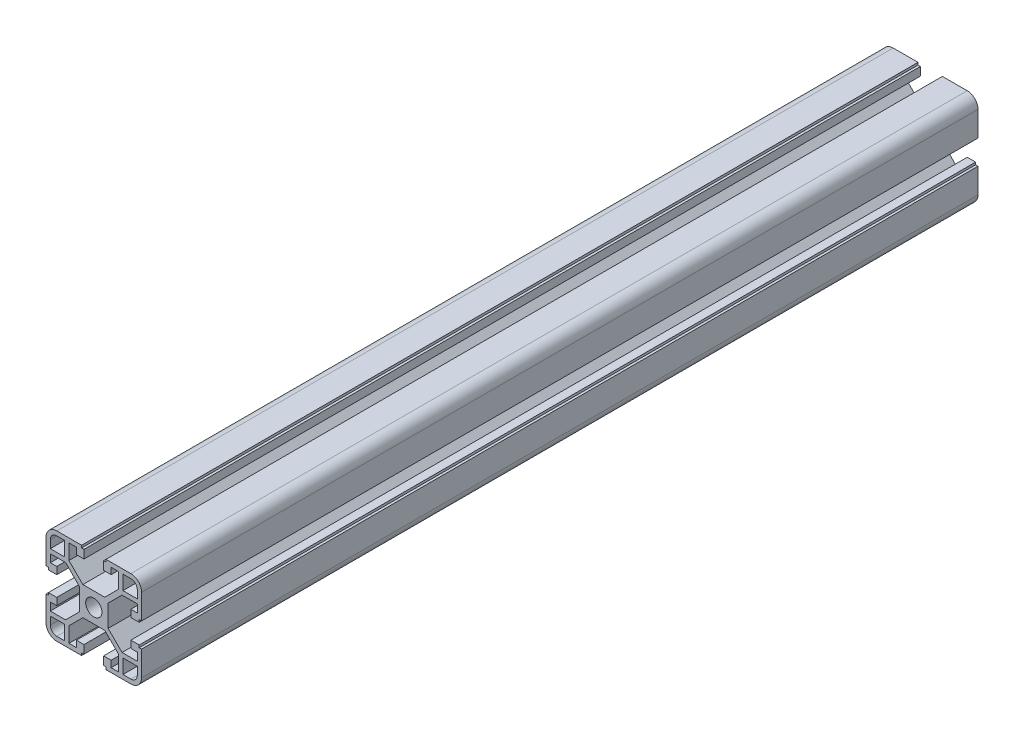
SolidWorks part; units mm, degrees
material "6063-T5"
ref_plane "Front Plane" through (0, 0, 0) normal (0, 0, 1) x (1, 0, 0)
ref_plane "Top Plane" through (0, 0, 0) normal (0, 1, 0) x (1, 0, 0)
ref_plane "Right Plane" through (0, 0, 0) normal (1, 0, 0) x (0, 0, -1)
sketch "Sketch3" plane through (0, 0, 0) normal (0, 0, 1) x (1, 0, 0)
  line L0 (17.9333, 92.7) -> (169.2667, 92.7) construction
  line L1 (-6, 6) -> (6, 6)
  line L2 (-6, 6) -> (-6, -6)
  line L3 (-6, -6) -> (6, -6)
  line L4 (6, 6) -> (6, -6)
  line L5 (0, 0) -> (20.1249, 20.1249) construction
  line L6 (4.5736, 4.5736) -> (11.4537, 11.4537) construction
  line L7 (5.2807, 3.8665) -> (12.0153, 10.6011)
  line L8 (3.8665, 5.2807) -> (10.7858, 12.2)
  line L13 (11.8142, 10.4) -> (18.2, 10.4)
  line L14 (6, 0) -> (23.1042, 0) construction
  line L15 (0, 6) -> (0, 13.9346) construction
  line L16 (4.5736, 4.5736) -> (11.8129, 11.8129) construction
  line L17 (5.2807, 3.8665) -> (12.52, 11.1058) construction
  line L18 (3.8665, 5.2807) -> (11.1058, 12.52) construction
  line L19 (10.4, 11.8142) -> (10.4, 18.2)
  line L20 (10.4, 18.2) -> (7.2581, 18.2)
  line L21 (-20, 20) -> (20, 20) construction
  line L22 (-20, 20) -> (-20, -20) construction
  line L23 (-20, -20) -> (20, -20) construction
  line L24 (20, 20) -> (20, -20) construction
  line L25 (7.2581, 18.2) -> (7.2581, 15.5)
  line L26 (7.2581, 15.5) -> (4.1, 15.5)
  line L27 (4.1, 15.5) -> (4.1, 19)
  line L28 (4.1, 19) -> (5.1, 19)
  line L29 (5.1, 19) -> (5.1, 20)
  line L30 (5.1, 20) -> (15.5, 20)
  line L31 (20, 15.5) -> (20, 5.1)
  line L32 (20, 5.1) -> (19, 5.1)
  line L33 (19, 5.1) -> (19, 4.1)
  line L34 (19, 4.1) -> (15.5, 4.1)
  line L35 (15.5, 4.1) -> (15.5, 7.1)
  line L36 (15.5, 7.1) -> (18.2, 7.1)
  line L37 (18.2, 7.1) -> (18.2, 10.4)
  line L42 (18.2, 12.2) -> (12.2, 12.2)
  line L43 (12.2, 18.2) -> (12.2, 18.2)
  line L44 (12.2, 18.2) -> (12.2, 18.2)
  line L45 (12.2, 18.2) -> (12.2, 18.2)
  line L46 (12.2, 18.2) -> (12.2, 18.2)
  line L47 (12.2, 18.2) -> (12.2, 18.2)
  line L48 (12.2, 18.2) -> (12.2, 18.2)
  line L49 (12.2, 18.2) -> (15.5, 18.2)
  line L50 (18.2, 15.5) -> (18.2, 12.2)
  line L51 (18.2, 12.2) -> (18.2, 12.2)
  line L52 (18.2, 12.2) -> (18.2, 12.2)
  line L53 (18.2, 12.2) -> (18.2, 12.2)
  line L54 (18.2, 12.2) -> (18.2, 12.2)
  line L55 (18.2, 12.2) -> (18.2, 12.2)
  line L56 (18.2, 12.2) -> (18.2, 12.2)
  line L57 (12.2, 12.2) -> (12.2, 18.2)
  line L58 (11.8142, 12.2) -> (18.2, 12.2) construction
  line L59 (12.2, 11.8142) -> (12.2, 18.2) construction
  line L60 (-18.2, 15.5) -> (-18.2, 12.2)
  line L61 (-12.2, 18.2) -> (-15.5, 18.2)
  line L62 (-12.2, 12.2) -> (-12.2, 18.2)
  line L63 (-18.2, 12.2) -> (-12.2, 12.2)
  line L64 (-11.8142, 10.4) -> (-18.2, 10.4)
  line L65 (-18.2, 7.1) -> (-18.2, 10.4)
  line L66 (-15.5, 7.1) -> (-18.2, 7.1)
  line L67 (-15.5, 4.1) -> (-15.5, 7.1)
  line L68 (-19, 4.1) -> (-15.5, 4.1)
  line L69 (-19, 5.1) -> (-19, 4.1)
  line L70 (-20, 5.1) -> (-19, 5.1)
  line L71 (-20, 15.5) -> (-20, 5.1)
  line L72 (-5.1, 20) -> (-15.5, 20)
  line L73 (-5.1, 19) -> (-5.1, 20)
  line L74 (-4.1, 19) -> (-5.1, 19)
  line L75 (-4.1, 15.5) -> (-4.1, 19)
  line L76 (-7.2581, 15.5) -> (-4.1, 15.5)
  line L77 (-7.2581, 18.2) -> (-7.2581, 15.5)
  line L78 (-10.4, 18.2) -> (-7.2581, 18.2)
  line L79 (-10.4, 11.8142) -> (-10.4, 18.2)
  line L80 (-10.4, 11.8142) -> (-4.5858, 6)
  line L81 (-11.8142, 10.4) -> (-6, 4.5858)
  line L82 (-18.2, -15.5) -> (-18.2, -12.2)
  line L83 (-18.2, -12.2) -> (-12.2, -12.2)
  line L84 (-12.2, -12.2) -> (-12.2, -18.2)
  line L85 (-12.2, -18.2) -> (-15.5, -18.2)
  line L86 (-20, -15.5) -> (-20, -5.1)
  line L87 (-20, -5.1) -> (-19, -5.1)
  line L88 (-19, -5.1) -> (-19, -4.1)
  line L89 (-19, -4.1) -> (-15.5, -4.1)
  line L90 (-15.5, -4.1) -> (-15.5, -7.1)
  line L91 (-15.5, -7.1) -> (-18.2, -7.1)
  line L92 (-18.2, -7.1) -> (-18.2, -10.4)
  line L93 (-11.8142, -10.4) -> (-18.2, -10.4)
  line L94 (-11.8142, -10.4) -> (-6, -4.5858)
  line L95 (-10.4, -11.8142) -> (-4.5858, -6)
  line L96 (-10.4, -11.8142) -> (-10.4, -18.2)
  line L97 (-10.4, -18.2) -> (-7.2581, -18.2)
  line L98 (-7.2581, -18.2) -> (-7.2581, -15.5)
  line L99 (-7.2581, -15.5) -> (-4.1, -15.5)
  line L100 (-4.1, -15.5) -> (-4.1, -19)
  line L101 (-4.1, -19) -> (-5.1, -19)
  line L102 (-5.1, -19) -> (-5.1, -20)
  line L103 (-5.1, -20) -> (-15.5, -20)
  line L104 (12.2, -18.2) -> (15.5, -18.2)
  line L105 (12.2, -12.2) -> (12.2, -18.2)
  line L106 (18.2, -12.2) -> (12.2, -12.2)
  line L107 (18.2, -15.5) -> (18.2, -12.2)
  line L108 (5.1, -20) -> (15.5, -20)
  line L109 (5.1, -19) -> (5.1, -20)
  line L110 (4.1, -19) -> (5.1, -19)
  line L111 (4.1, -15.5) -> (4.1, -19)
  line L112 (7.2581, -15.5) -> (4.1, -15.5)
  line L113 (10.4, -18.2) -> (7.2581, -18.2)
  line L114 (7.2581, -18.2) -> (7.2581, -15.5)
  line L115 (10.4, -11.8142) -> (10.4, -18.2)
  line L116 (10.4, -11.8142) -> (4.5858, -6)
  line L117 (11.8142, -10.4) -> (6, -4.5858)
  line L118 (11.8142, -10.4) -> (18.2, -10.4)
  line L119 (18.2, -7.1) -> (18.2, -10.4)
  line L120 (20, -15.5) -> (20, -5.1)
  line L121 (20, -5.1) -> (19, -5.1)
  line L122 (19, -5.1) -> (19, -4.1)
  line L123 (15.5, -7.1) -> (18.2, -7.1)
  line L124 (15.5, -4.1) -> (15.5, -7.1)
  line L125 (19, -4.1) -> (15.5, -4.1)
  circle A0 centre (0, 0) radius 3.4
  arc A1 (15.5, 20) -> (20, 15.5) centre (15.5, 15.5) cw
  arc A2 (15.5, 18.2) -> (18.2, 15.5) centre (15.5, 15.5) cw
  arc A3 (-15.5, 18.2) -> (-18.2, 15.5) centre (-15.5, 15.5) ccw
  arc A4 (-15.5, 20) -> (-20, 15.5) centre (-15.5, 15.5) ccw
  arc A5 (-15.5, -18.2) -> (-18.2, -15.5) centre (-15.5, -15.5) cw
  arc A6 (-15.5, -20) -> (-20, -15.5) centre (-15.5, -15.5) cw
  arc A7 (15.5, -18.2) -> (18.2, -15.5) centre (15.5, -15.5) ccw
  arc A8 (15.5, -20) -> (20, -15.5) centre (15.5, -15.5) ccw
  point P7 (6, 0)
  point P8 (0, 6)
  point P36 (0, 20)
  point P37 (-20, 0)
  dimension "D3" = 6.8
  dimension "D28" = 4.5
  dimension "D1" = 12
  dimension "D2" = 12
  dimension "D6" = 10.4
  dimension "D7" = 10.4
  dimension "D8" = 40
  dimension "D9" = 40
  dimension "D10" = 1
  dimension "D11" = 1
  dimension "D12" = 1.8
  dimension "D13" = 1.8
  dimension "D14" = 2
  dimension "D17" = 1.8
  dimension "D18" = 1.8
  dimension "D19" = 1
  dimension "D20" = 1
  dimension "D21" = 3.5
  dimension "D22" = 5.1
  dimension "D23" = 4.1
  dimension "D24" = 3
  dimension "D25" = 3.5
  dimension "D26" = 4.1
  dimension "D27" = 5.1
  dimension "D4" = 1
  dimension "D5" = 1
  dimension "D29" = 1.8
extrude "Boss-Extrude1" add sketch "Sketch3" along normal blind 350
